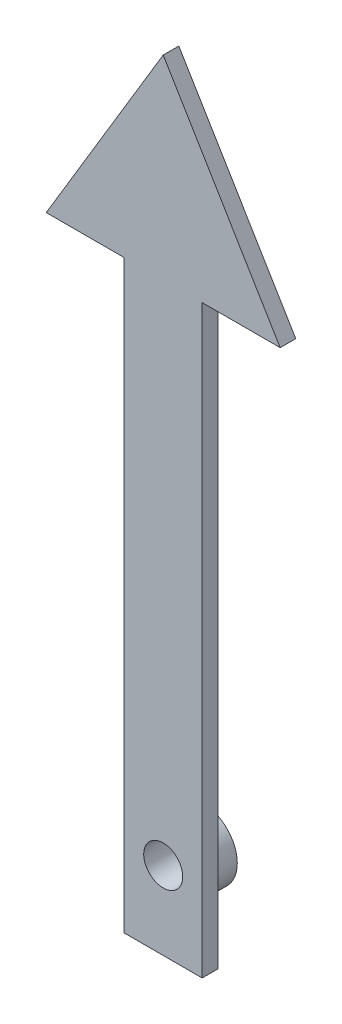
SolidWorks part; units mm, degrees
ref_plane "Front Plane" through (0, 0, 0) normal (0, 0, 1) x (1, 0, 0)
ref_plane "Top Plane" through (0, 0, 0) normal (0, 1, 0) x (1, 0, 0)
ref_plane "Right Plane" through (0, 0, 0) normal (1, 0, 0) x (0, 0, -1)
sketch "Sketch1" plane through (0, 0, 0) normal (0, 0, 1) x (1, 0, 0)
  line L4 (1.27, 0) -> (1.27, 19.05)
  line L6 (0, 25.4) -> (3.81, 19.05)
  line L7 (3.81, 19.05) -> (1.27, 19.05)
  line L8 (0, -1.4173) -> (0, 27.9435) construction
  line L9 (1.27, 0) -> (-1.27, 0)
  line L10 (-3.81, 19.05) -> (-1.27, 19.05)
  line L11 (-1.27, 0) -> (-1.27, 19.05)
  line L12 (0, 25.4) -> (-3.81, 19.05)
  point P14 (0, 0)
  dimension "D1" = 1.27
  dimension "D2" = 25.4
  dimension "D3" = 19.05
  dimension "D4" = 3.81
extrude "Boss-Extrude1" add sketch "Sketch1" along normal blind 0.508
sketch "Sketch3" plane through (0, 0, 0.508) normal (0, 0, 1) x (1, 0, 0)
  circle A0 centre (0, 2.54) radius 0.635
  dimension "D2" = 1.27
  dimension "D1" = 2.54
extrude "Cut-Extrude1" cut sketch "Sketch3" against normal through all contours A0
sketch "Sketch5" plane through (0, 0, 0) normal (0, 0, -1) x (-1, 0, 0)
  circle A0 centre (0, 2.54) radius 0.635
  circle A1 centre (0, 2.54) radius 1.143
  dimension "D1" = 2.286
  dimension "D2" = 1.27
extrude "Boss-Extrude2" add sketch "Sketch5" along normal blind 0.762
